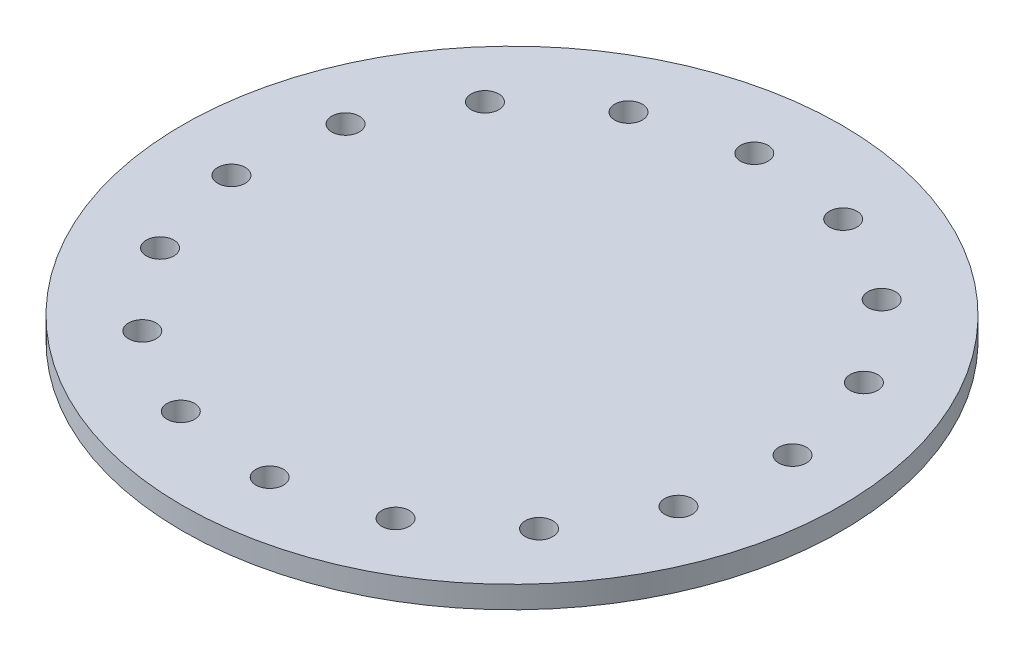
SolidWorks part; units mm, degrees
ref_plane "Front Plane" through (0, 0, 0) normal (0, 0, 1) x (1, 0, 0)
ref_plane "Top Plane" through (0, 0, 0) normal (0, 1, 0) x (1, 0, 0)
ref_plane "Right Plane" through (0, 0, 0) normal (1, 0, 0) x (0, 0, -1)
sketch "Sketch1" plane through (0, 0, 0) normal (0, 1, 0) x (1, 0, 0)
  circle A0 centre (0, 0) radius 29.8611
  dimension "D1" = 59.7222
extrude "Boss-Extrude1" add sketch "Sketch1" along normal mid plane 2
sketch "Sketch2" plane through (0, 1, 0) normal (0, 1, 0) x (1, 0, 0)
  circle A0 centre (1.7336, -23.6866) radius 1.25 construction
  circle A1 centre (-7.4628, -22.547) radius 1.25 construction
  circle A2 centre (-15.5231, -17.9748) radius 1.25 construction
  circle A3 centre (-21.2202, -10.6661) radius 1.25 construction
  circle A4 centre (-23.6866, -1.7336) radius 1.25 construction
  circle A5 centre (-22.547, 7.4628) radius 1.25 construction
  circle A6 centre (-17.9748, 15.5231) radius 1.25 construction
  circle A7 centre (-10.6661, 21.2202) radius 1.25 construction
  circle A8 centre (-1.7336, 23.6866) radius 1.25 construction
  circle A9 centre (10.6661, -21.2202) radius 1.25 construction
  circle A10 centre (17.9748, -15.5231) radius 1.25 construction
  circle A11 centre (22.547, -7.4628) radius 1.25 construction
  circle A12 centre (23.6866, 1.7336) radius 1.25 construction
  circle A13 centre (21.2202, 10.6661) radius 1.25 construction
  circle A14 centre (15.5231, 17.9748) radius 1.25 construction
  circle A15 centre (7.4628, 22.547) radius 1.25 construction
  circle A16 centre (1.7336, -23.6866) radius 1.25
  circle A17 centre (-7.4628, -22.547) radius 1.25
  circle A18 centre (-15.5231, -17.9748) radius 1.25
  circle A19 centre (-21.2202, -10.6661) radius 1.25
  circle A20 centre (-23.6866, -1.7336) radius 1.25
  circle A21 centre (-22.547, 7.4628) radius 1.25
  circle A22 centre (-17.9748, 15.5231) radius 1.25
  circle A23 centre (-10.6661, 21.2202) radius 1.25
  circle A24 centre (-1.7336, 23.6866) radius 1.25
  circle A25 centre (10.6661, -21.2202) radius 1.25
  circle A26 centre (17.9748, -15.5231) radius 1.25
  circle A27 centre (22.547, -7.4628) radius 1.25
  circle A28 centre (23.6866, 1.7336) radius 1.25
  circle A29 centre (21.2202, 10.6661) radius 1.25
  circle A30 centre (15.5231, 17.9748) radius 1.25
  circle A31 centre (7.4628, 22.547) radius 1.25
extrude "Cut-Extrude1" cut sketch "Sketch2" against normal through all both and the other way through all
